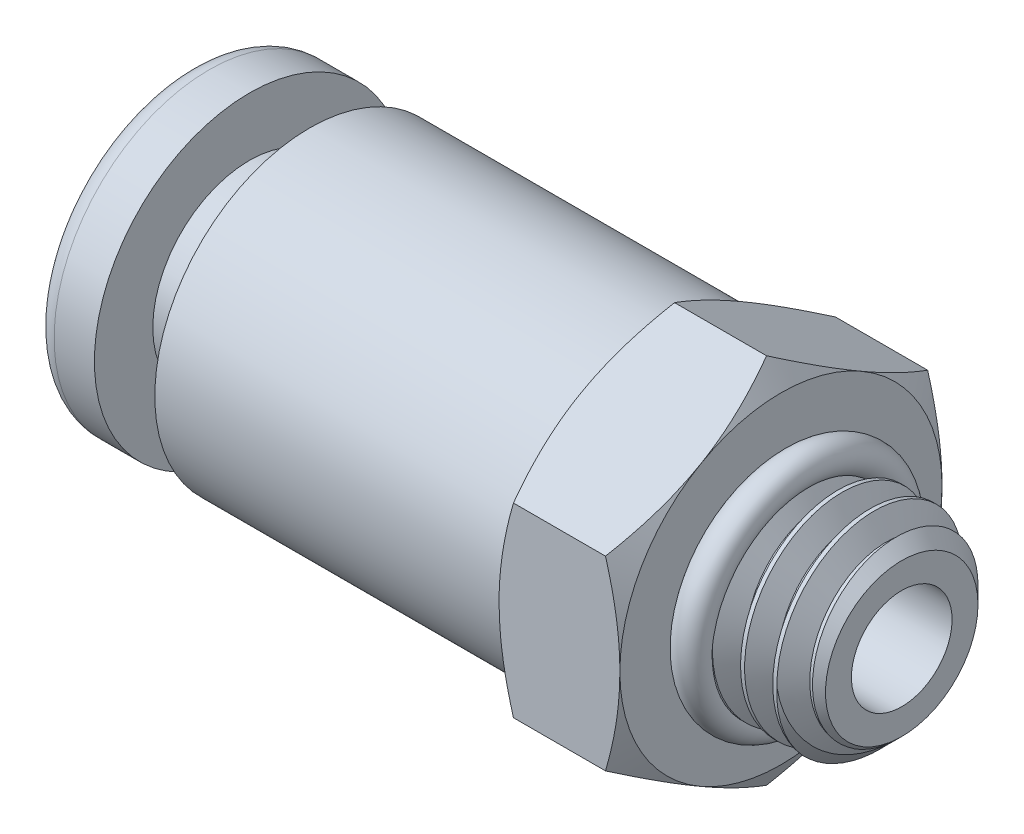
SolidWorks part; units mm, degrees
ref_plane "Front Plane" through (0, 0, 0) normal (0, 0, 1) x (1, 0, 0)
ref_plane "Top Plane" through (0, 0, 0) normal (0, 1, 0) x (1, 0, 0)
ref_plane "Right Plane" through (0, 0, 0) normal (1, 0, 0) x (0, 0, -1)
sketch "Sketch0" plane through (0, 0, 0) normal (0, 0, -1) x (-1, 0, 0)
  line L0 (0, 0) -> (-17.7, 0) construction
  line L1 (0, 3.85) -> (0, -3.85) construction
  line L2 (-13.3, 2) -> (-13.3, -2) construction
  line L3 (-14.7, 2.5) -> (-14.7, -2.5) construction
  line L4 (-8.85, 4) -> (-8.85, -4) construction
  line L5 (-17.7, 1.25) -> (-17.7, -1.25) construction
  point P3 (-13.3, 0)
  point P11 (-8.85, 0)
  point P16 (-14.7, 0)
  point P17 (-14.7, 0)
  dimension "L" = 17.7
  dimension "M" = 13.3
  dimension "A" = 14.7
  dimension "D" = 7.7
  dimension "Tube OD" = 4
  dimension "Thread OD" = 5
  dimension "H" = 8
  dimension "ID" = 2.5
  dimension "Thread Length" = 3
sketch "Sketch1" plane through (0, 0, 0) normal (0, 0, -1) x (-1, 0, 0)
  line L0 (0, 3.35) -> (0, 2.5)
  line L1 (-0.5, 3.85) -> (-1.5, 3.85)
  line L2 (-1.5, 3.85) -> (-1.5, 2.4)
  line L3 (-1.5, 2.4) -> (-3, 2.4)
  line L4 (-3, 2.4) -> (-3, 3.85)
  line L5 (-3, 3.85) -> (-14.7, 3.85)
  line L6 (-14.7, 3.85) -> (-14.7, 0)
  line L7 (0, 0) -> (-17.7, 0) construction
  line L8 (-14.7, 0) -> (-13.3, 0)
  line L9 (-13.3, 2) -> (-13.3, 0)
  line L10 (0, 0) -> (-17.7, 0) construction
  line L11 (-13.3, 2) -> (-0.5, 2)
  line L12 (0, 3.85) -> (0, -3.85) construction
  line L14 (-14.7, 2.5) -> (-14.7, -2.5) construction
  arc A0 (0, 3.35) -> (-0.5, 3.85) centre (-0.5, 3.35) ccw
  arc A1 (-0.5, 2) -> (0, 2.5) centre (-0.5, 2.5) ccw
  point P15 (0, 3.85)
  point P19 (0, 3.85)
  point P25 (0, 2)
  dimension "R" = 0.5
  dimension "D1" = 1.5
  dimension "D3" = 4.8
  dimension "D2" = 1.5
revolve "Revolve2" add sketch "Sketch1" angle 360 about L10
ref_plane "Plane1" through (14.7, 0, 0) normal (1, 0, 0) x (0, 0, -1)
sketch "Sketch2" plane through (14.7, 0, 0) normal (1, 0, 0) x (0, 0, -1)
  circle A0 centre (0, 0) radius 2.5
  point P5 (0, -2.5)
extrude "Extrude1" add sketch "Sketch2" along normal up to vertex (3 mm away) separate body up to point (17.7, 0, 0)
sketch "Sketch3" plane through (17.7, 0, 0) normal (1, 0, 0) x (0, 0, -1)
  circle A1 centre (0, 0) radius 2.5
  circle A2 centre (0, 0) radius 2.5
  point P0 (0, 2.5)
  dimension "D1" = 0
curve "Helix/Spiral1" pitch 0.8 height 5.3 turns 6.625 parameters "Height"=5.3, "Pitch"=0.8
sketch "Sketch4" plane through (0, 0, 0) normal (0, 0, -1) x (-1, 0, 0)
  line L0 (-18.45, 2.5866) -> (-18.05, 1.8938) construction
  line L1 (-18.05, 1.8938) -> (-17.65, 2.5866) construction
  line L2 (-17.65, 2.5866) -> (-18.45, 2.5866) construction
  line L3 (-18.4, 2.5) -> (-17.7, 2.5) construction
  line L4 (-18.05, 2.5866) -> (-18.05, 2.5) construction
  line L5 (-18.05, 2.5) -> (-18.05, 1.9804) construction
  line L6 (-18.05, 1.9804) -> (-18.05, 1.8938) construction
  line L7 (-18.1, 1.9804) -> (-18, 1.9804)
  line L8 (-17.65, 2.5866) -> (-18.4, 2.5)
  line L9 (-17.65, 2.5866) -> (-18, 1.9804)
  line L10 (-18.4, 2.5) -> (-18.1, 1.9804)
  line L11 (-18.05, 1.8938) -> (-18.05, -2.5) construction
  line L12 (-18.05, -2.5) -> (-17.25, -2.5) construction
  line L13 (-17.25, -2.5) -> (-16.45, -2.5) construction
  line L14 (-16.45, -2.5) -> (-15.65, -2.5) construction
  line L15 (-15.65, -2.5) -> (-14.85, -2.5) construction
  line L16 (-17.7, -2.5) -> (-14.7, -2.5) construction
  dimension "D1" = 0.8
  dimension "D2" = 0.1
sketch "Sketch5" plane through (17.7, 0, 0) normal (1, 0, 0) x (0, 0, -1)
  circle A0 centre (0, 0) radius 1.8938
extrude "Extrude2" cut sketch "Sketch5" against normal up to vertex (3 mm away) draft 45 flip side to cut up to point (14.7, 0, 0)
sweep "Cut-Sweep1" cut profiles "Sketch4" path "Helix/Spiral1"
sketch "Sketch7" plane through (17.7, 0, 0) normal (1, 0, 0) x (0, 0, -1)
  circle A0 centre (0, 0) radius 1.25
extrude "Extrude4" cut sketch "Sketch7" against normal up to vertex (17.7 mm away) up to point (0, 0, 0)
sketch "Sketch8" plane through (14.7, 0, 0) normal (1, 0, 0) x (0, 0, -1)
  line L1 (0, 4.6188) -> (-4, 2.3094)
  line L2 (-4, 2.3094) -> (-4, -2.3094)
  line L3 (-4, -2.3094) -> (0, -4.6188)
  line L4 (0, -4.6188) -> (4, -2.3094)
  line L5 (4, -2.3094) -> (4, 2.3094)
  line L6 (4, 2.3094) -> (0, 4.6188)
  circle A0 centre (0, 0) radius 4 construction
  circle A1 centre (0, 0) radius 3.85 construction
  circle A3 centre (0, 0) radius 3.85
extrude "Extrude5" add sketch "Sketch8" against normal blind 3
sketch "Sketch9" plane through (14.7, 0, 0) normal (1, 0, 0) x (0, 0, -1)
  circle A0 centre (0, 0) radius 4 construction
  circle A1 centre (0, 0) radius 4
extrude "Extrude6" cut sketch "Sketch9" against normal up to vertex (3 mm away) draft 60 flip side to cut up to point (11.7, 4.6188, 0)
sketch "Sketch10" plane through (11.7, 0, 0) normal (-1, 0, 0) x (0, 0, 1)
  circle A1 centre (0, 0) radius 4
  circle A2 centre (0, 0) radius 4
  dimension "D1" = 0
extrude "Extrude7" cut sketch "Sketch10" against normal up to vertex (3 mm away) draft 60 flip side to cut up to point (14.7, 4.6188, 0)
combine bodies "Combine1" operation type add bodies to combine 116 109
sketch "Sketch11" plane through (0, 0, 0) normal (0, 0, 1) x (1, 0, 0)
  line L0 (14.7, 2.5866) -> (15.5, 2.5866) construction
  line L1 (14.7, 2.5) -> (14.7, -2.5) construction
  line L2 (17.65, 2.5866) -> (18.45, 2.5866) construction
  line L4 (14.7, 0) -> (17.7, 0) construction
  circle A0 centre (15.1, 2.5866) radius 0.4
revolve "Revolve3" add sketch "Sketch11" angle 360 about L4
equation "\"Height@Helix/Spiral1\" = \"Pitch@Helix/Spiral1\" +  ( \"Thread Length@Sketch0\" * 1.5 ) "
equation "\"D1@Sketch4\" = \"Pitch@Helix/Spiral1\""
equation "\"D2@Sketch4\" = \"D1@Sketch4\" * 1 / 8"
